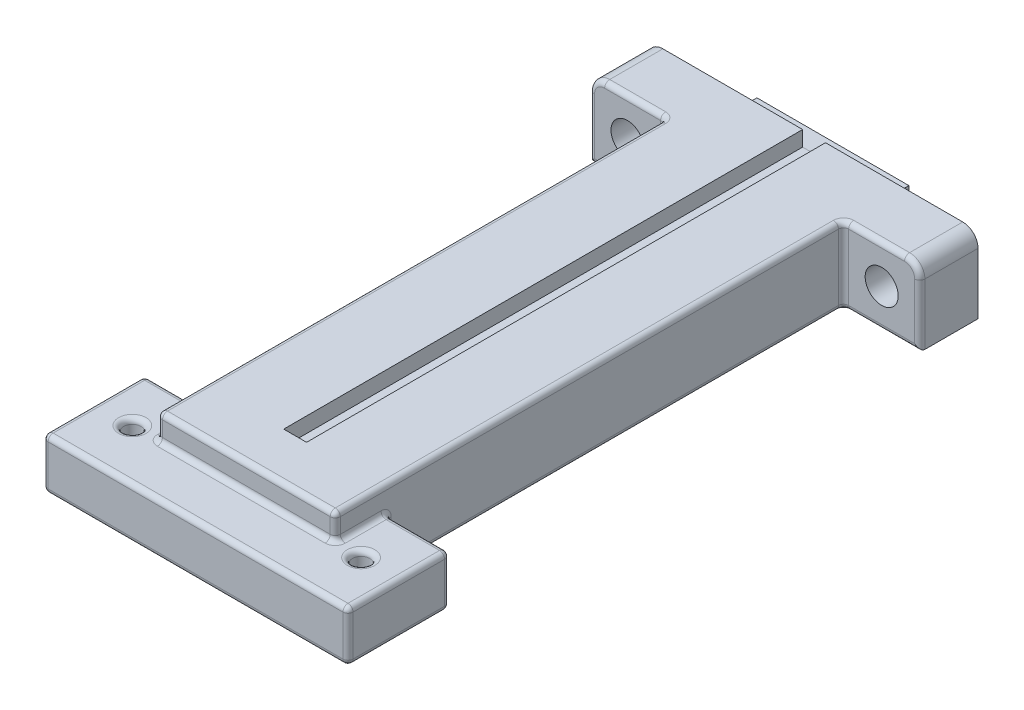
SolidWorks part; units mm, degrees
ref_plane "Front Plane" through (0, 0, 0) normal (0, 0, 1) x (1, 0, 0)
ref_plane "Top Plane" through (0, 0, 0) normal (0, 1, 0) x (1, 0, 0)
ref_plane "Right Plane" through (0, 0, 0) normal (1, 0, 0) x (0, 0, -1)
sketch "Sketch1" plane through (0, 0, 0) normal (0, 0, 1) x (1, 0, 0)
  line L1 (0, 0) -> (65, 0)
  line L2 (0, 0) -> (0, 15)
  line L3 (0, 15) -> (65, 15)
  line L4 (65, 0) -> (65, 15)
  circle A0 centre (7.5, 7.5) radius 3.25
  circle A1 centre (57.5, 7.5) radius 3.25
  dimension "D7" = 6.5
  dimension "D8" = 6.5
  dimension "D1" = 65
  dimension "D2" = 15
  dimension "D3" = 7.5
  dimension "D4" = 7.5
  dimension "D5" = 7.5
  dimension "D6" = 7.5
extrude "Boss-Extrude1" add sketch "Sketch1" along normal blind 11.45
sketch "Sketch2" plane through (0, 0, 11.45) normal (0, 0, 1) x (1, 0, 0)
  line L0 (0, 0) -> (65, 0) construction
  line L1 (15, 0) -> (50, 0)
  line L2 (15, 0) -> (15, 15)
  line L3 (15, 15) -> (50, 15)
  line L4 (50, 0) -> (50, 15)
  line L5 (65, 15) -> (0, 15) construction
  dimension "D1" = 35
  dimension "D2" = 15
extrude "Boss-Extrude2" add sketch "Sketch2" along normal blind 100
sketch "Sketch3" plane through (0, 0, 0) normal (0, -1, 0) x (-1, 0, 0)
  line L1 (-62.5, -121.45) -> (-2.5, -121.45)
  line L2 (-62.5, -121.45) -> (-62.5, -101.45)
  line L3 (-62.5, -101.45) -> (-2.5, -101.45)
  line L4 (-2.5, -121.45) -> (-2.5, -101.45)
  line L5 (-15, -111.45) -> (-15, -11.45) construction
  dimension "D1" = 60
  dimension "D2" = 20
  dimension "D3" = 12.5
extrude "Boss-Extrude3" add sketch "Sketch3" against normal blind 10
sketch "Sketch4" plane through (0, 15, 0) normal (0, 1, 0) x (1, 0, 0)
  line L0 (62.5, -101.45) -> (62.5, -121.45) construction
  line L1 (2.5, -121.45) -> (2.5, -101.45) construction
  circle A0 centre (10, -111.3749) radius 1.7
  circle A1 centre (55, -111.3749) radius 1.7
  dimension "D1" = 3.4
  dimension "D2" = 3.4
  dimension "D3" = 45
  dimension "D4" = 7.5
  dimension "D5" = 7.5
extrude "Cut-Extrude1" cut sketch "Sketch4" against normal blind 31.45
sketch "Sketch5" plane through (0, 0, 0) normal (0, 0, -1) x (-1, 0, 0)
  line L0 (-65, 15) -> (0, 15) construction
  line L1 (-17.5, 11.9) -> (-47.4, 11.9)
  line L2 (-17.5, 11.9) -> (-17.5, 4)
  line L3 (-17.5, 4) -> (-47.4, 4)
  line L4 (-47.4, 11.9) -> (-47.4, 4)
  line L5 (-65, 0) -> (-65, 15) construction
  dimension "D1" = 29.9
  dimension "D2" = 7.9
  dimension "D3" = 3.1
  dimension "D4" = 17.6
extrude "Boss-Extrude4" add sketch "Sketch5" along normal blind 4
sketch "Sketch6" plane through (0, 15, 0) normal (0, 1, 0) x (1, 0, 0)
  line L0 (17.5, 0) -> (47.4, 0) construction
  line L1 (30.5, -102.0971) -> (35, -102.0971)
  line L2 (30.5, -102.0971) -> (30.5, 0)
  line L3 (30.5, 0) -> (35, 0)
  line L4 (35, -102.0971) -> (35, 0)
  line L5 (50, -111.45) -> (50, -11.45) construction
  dimension "D1" = 4.5
  dimension "D2" = 15
extrude "Cut-Extrude2" cut sketch "Sketch6" against normal blind 3
fillet "Fillet1" radius 3 2 edges at (65, 15, 5.725) (0, 15, 5.725)
fillet "Fillet2" radius 1 38 edges at (65, 6, 11.45) (64.1213, 14.1213, 11.45) (7.5, 0, 11.45) (56, 15, 11.45) (57.5, 0, 11.45) (9, 15, 11.45) (0.8787, 14.1213, 11.45) (15, 7.5, 11.45) (15, 15, 61.45) (15, 0, 56.45) (32.5, 0, 121.45) (32.5, 10, 121.45) (2.5, 5, 121.45) (2.5, 0, 111.45) (2.5, 10, 111.45) (62.5, 5, 121.45) (62.5, 0, 111.45) (62.5, 10, 111.45) (56.25, 10, 101.45) (56.25, 0, 101.45) (62.5, 5, 101.45) (2.5, 5, 101.45) (8.75, 0, 101.45) (8.75, 10, 101.45) (15, 5, 101.45) (15, 10, 106.45) (55, 10, 113.0749) (10, 10, 113.0749) (50, 15, 61.45) (50, 7.5, 11.45) (50, 0, 56.45) (50, 5, 101.45) (50, 10, 106.45) (32.5, 15, 111.45) (50, 12.5, 111.45) (32.5, 10, 111.45) (15, 12.5, 111.45) (0, 6, 11.45)
